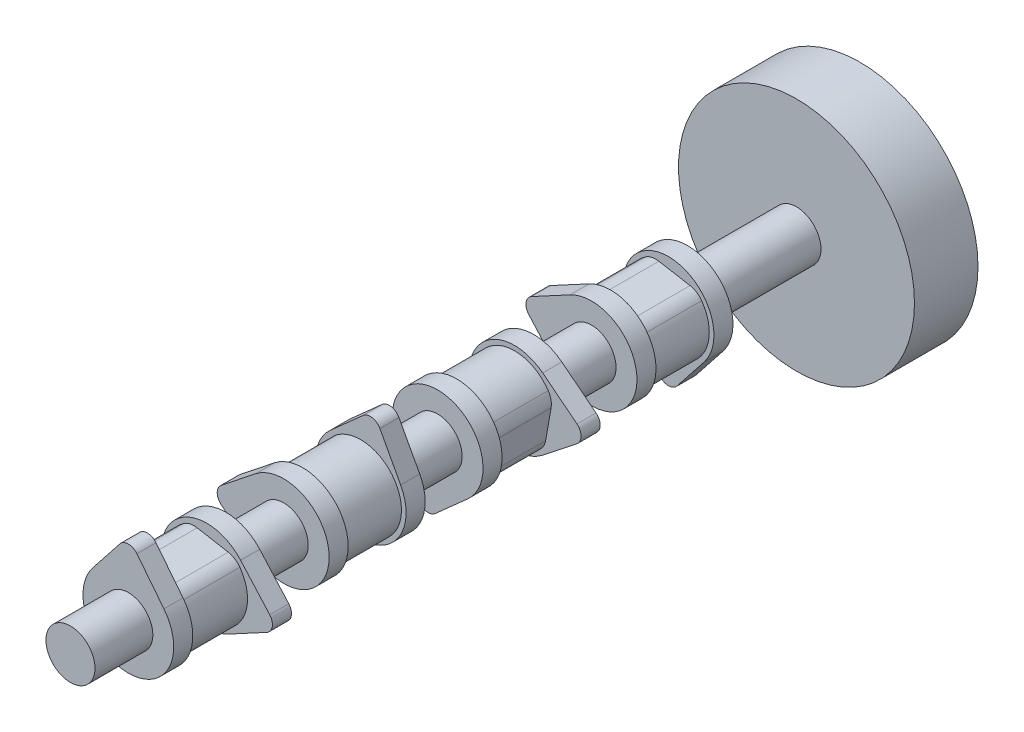
SolidWorks part; units mm, degrees
ref_plane "Alzado" through (0, 0, 0) normal (0, 0, 1) x (1, 0, 0)
ref_plane "Planta" through (0, 0, 0) normal (0, 1, 0) x (1, 0, 0)
ref_plane "Vista lateral" through (0, 0, 0) normal (1, 0, 0) x (0, 0, -1)
sketch "Croquis1" plane through (0, 0, 0) normal (0, 0, 1) x (1, 0, 0)
  circle A0 centre (0, 0) radius 65
  dimension "D1" = 130
extrude "Saliente-Extruir2" add sketch "Croquis1" along normal blind 35
sketch "Croquis2" plane through (0, 0, 35) normal (0, 0, 1) x (1, 0, 0)
  circle A0 centre (0, 0) radius 13.5
  dimension "D1" = 27
extrude "Saliente-Extruir3" add sketch "Croquis2" along normal blind 400
ref_plane "Plano1" through (0, 0, 392.6) normal (0, 0, 1) x (1, 0, 0)
sketch "Croquis3" plane through (0, 0, 392.6) normal (0, 0, 1) x (1, 0, 0)
  line L0 (0, -25) -> (0, 36.65) construction
  line L3 (-19.617, 15.4976) -> (-4.7081, 34.3694)
  line L4 (4.7081, 34.3694) -> (19.617, 15.4976)
  line L5 (0, 0) -> (7.2218, 0) construction
  circle A0 centre (0, 0) radius 13.5
  arc A1 (-19.617, 15.4976) -> (19.617, 15.4976) centre (0, 0) ccw
  arc A2 (4.7081, 34.3694) -> (-4.7081, 34.3694) centre (0, 30.65) ccw
  dimension "D1" = 50
  dimension "D2" = 27
  dimension "D4" = 6
  dimension "D3" = 61.65
extrude "Saliente-Extruir4" add sketch "Croquis3" along normal blind 10.5
ref_plane "Plano2" through (0, 0, 349.4) normal (0, 0, 1) x (1, 0, 0)
sketch "Croquis4" plane through (0, 0, 349.4) normal (0, 0, 1) x (1, 0, 0)
  line L0 (-24.6202, 4.3412) -> (36.0932, -6.3642) construction
  line L1 (18.6686, 16.6278) -> (34.6648, -1.3316)
  line L2 (33.0297, -10.6047) -> (11.8557, -22.0101)
  line L3 (0, 0) -> (7.2218, 0) construction
  circle A0 centre (0, 0) radius 13.5
  arc A1 (18.6686, 16.6278) -> (11.8557, -22.0101) centre (0, 0) ccw
  arc A2 (33.0297, -10.6047) -> (34.6648, -1.3316) centre (30.1844, -5.3223) ccw
  dimension "D1" = 50
  dimension "D2" = 27
  dimension "D3" = 6
  dimension "D4" = 61.65
  dimension "D5" = 10
extrude "Saliente-Extruir6" add sketch "Croquis4" along normal blind 10.5
ref_plane "Plano3" through (0, 0, 307) normal (0, 0, 1) x (1, 0, 0)
ref_plane "Plano4" through (0, 0, 264.6) normal (0, 0, 1) x (1, 0, 0)
ref_plane "Plano5" through (0, 0, 222.2) normal (0, 0, 1) x (1, 0, 0)
ref_plane "Plano6" through (0, 0, 179.8) normal (0, 0, 1) x (1, 0, 0)
ref_plane "Plano7" through (0, 0, 137.4) normal (0, 0, 1) x (1, 0, 0)
ref_plane "Plano8" through (0, 0, 95) normal (0, 0, 1) x (1, 0, 0)
sketch "Croquis5" plane through (0, 0, 307) normal (0, 0, 1) x (1, 0, 0)
  line L0 (25, 0) -> (-36.65, 0) construction
  line L1 (-15.4976, -19.617) -> (-34.3694, -4.7081)
  line L2 (-34.3694, 4.7081) -> (-15.4976, 19.617)
  line L3 (0, 0) -> (7.246, 0) construction
  circle A0 centre (0, 0) radius 13.5
  arc A1 (-15.4976, -19.617) -> (-15.4976, 19.617) centre (0, 0) ccw
  arc A2 (-34.3694, 4.7081) -> (-34.3694, -4.7081) centre (-30.65, 0) ccw
  point P10 (0, 0)
  dimension "D1" = 50
  dimension "D2" = 27
  dimension "D3" = 6
  dimension "D4" = 61.65
  dimension "D5" = 180
extrude "Saliente-Extruir7" add sketch "Croquis5" along normal blind 10.5
sketch "Croquis6" plane through (0, 0, 264.6) normal (0, 0, 1) x (1, 0, 0)
  line L0 (-4.3412, -24.6202) -> (6.3642, 36.0932) construction
  line L1 (-16.6278, 18.6686) -> (1.3316, 34.6648)
  line L2 (10.6047, 33.0297) -> (22.0101, 11.8557)
  line L3 (0, 0) -> (7.2218, 0) construction
  circle A0 centre (0, 0) radius 13.5
  arc A1 (-16.6278, 18.6686) -> (22.0101, 11.8557) centre (0, 0) ccw
  arc A2 (10.6047, 33.0297) -> (1.3316, 34.6648) centre (5.3223, 30.1844) ccw
  point P10 (0, 0)
  dimension "D1" = 50
  dimension "D2" = 27
  dimension "D3" = 6
  dimension "D4" = 61.65
  dimension "D5" = 80
extrude "Saliente-Extruir8" add sketch "Croquis6" along normal blind 10.5
sketch "Croquis7" plane through (0, 0, 222.2) normal (0, 0, 1) x (1, 0, 0)
  line L0 (4.3412, 24.6202) -> (-6.3642, -36.0932) construction
  line L1 (16.6278, -18.6686) -> (-1.3316, -34.6648)
  line L2 (-10.6047, -33.0297) -> (-22.0101, -11.8557)
  line L3 (0, 0) -> (7.2218, 0) construction
  circle A0 centre (0, 0) radius 13.5
  arc A1 (16.6278, -18.6686) -> (-22.0101, -11.8557) centre (0, 0) ccw
  arc A2 (-10.6047, -33.0297) -> (-1.3316, -34.6648) centre (-5.3223, -30.1844) ccw
  point P10 (0, 0)
  dimension "D1" = 50
  dimension "D2" = 27
  dimension "D3" = 6
  dimension "D4" = 61.65
  dimension "D5" = 260
extrude "Saliente-Extruir9" add sketch "Croquis7" along normal blind 10.5
sketch "Croquis8" plane through (0, 0, 179.8) normal (0, 0, 1) x (1, 0, 0)
  line L0 (-25, 0) -> (36.65, 0) construction
  line L1 (15.4976, 19.617) -> (34.3694, 4.7081)
  line L2 (34.3694, -4.7081) -> (15.4976, -19.617)
  line L3 (0, 0) -> (-65.5159, 0) construction
  circle A0 centre (0, 0) radius 13.5
  arc A1 (15.4976, 19.617) -> (15.4976, -19.617) centre (0, 0) ccw
  arc A2 (34.3694, -4.7081) -> (34.3694, 4.7081) centre (30.65, 0) ccw
  point P10 (0, 0)
  dimension "D1" = 50
  dimension "D2" = 27
  dimension "D3" = 6
  dimension "D4" = 61.65
  dimension "D5" = 180
extrude "Saliente-Extruir10" add sketch "Croquis8" along normal blind 10.5
sketch "Croquis9" plane through (0, 0, 137.4) normal (0, 0, 1) x (1, 0, 0)
  line L0 (24.6202, -4.3412) -> (-36.0932, 6.3642) construction
  line L1 (-18.6686, -16.6278) -> (-34.6648, 1.3316)
  line L2 (-33.0297, 10.6047) -> (-11.8557, 22.0101)
  line L3 (0, 0) -> (-72.796, 0) construction
  circle A0 centre (0, 0) radius 13.5
  arc A1 (-18.6686, -16.6278) -> (-11.8557, 22.0101) centre (0, 0) ccw
  arc A2 (-33.0297, 10.6047) -> (-34.6648, 1.3316) centre (-30.1844, 5.3223) ccw
  point P10 (0, 0)
  dimension "D1" = 50
  dimension "D2" = 27
  dimension "D3" = 6
  dimension "D4" = 61.65
  dimension "D5" = 10
extrude "Saliente-Extruir11" add sketch "Croquis9" along normal blind 10.5
sketch "Croquis10" plane through (0, 0, 95) normal (0, 0, 1) x (1, 0, 0)
  line L0 (0, 25) -> (0, -36.65) construction
  line L1 (19.617, -15.4976) -> (4.7081, -34.3694)
  line L2 (-4.7081, -34.3694) -> (-19.617, -15.4976)
  line L3 (0, 0) -> (-74.8277, 0) construction
  circle A0 centre (0, 0) radius 13.5
  arc A1 (19.617, -15.4976) -> (-19.617, -15.4976) centre (0, 0) ccw
  arc A2 (-4.7081, -34.3694) -> (4.7081, -34.3694) centre (0, -30.65) ccw
  point P10 (0, 0)
  dimension "D1" = 50
  dimension "D2" = 27
  dimension "D3" = 6
  dimension "D4" = 61.65
  dimension "D5" = 90
extrude "Saliente-Extruir12" add sketch "Croquis10" along normal blind 10.5
sketch "Croquis11" plane through (0, 0, 359.9) normal (0, 0, 1) x (1, 0, 0)
  line L0 (-5.3022, 20.1174) -> (11.863, 17.0907)
  line L1 (0, 0) -> (11.6898, 0) construction
  line L2 (0, 0) -> (3.2804, 18.6041) construction
  line L3 (0, 0) -> (8.2085, -1.4474) construction
  arc A0 (-12.6923, 18.5178) -> (18.2603, 13.06) centre (0, 0) ccw
  arc A1 (11.863, 17.0907) -> (18.2603, 13.06) centre (10.1265, 7.2426) cw
  arc A2 (-5.3022, 20.1174) -> (-12.6923, 18.5178) centre (-7.0387, 10.2693) ccw
  point P5 (0, -22.45)
  dimension "D1" = 44.9
  dimension "D3" = 10
  dimension "D2" = 41
  dimension "D4" = 18.8911
  dimension "D5" = 10
extrude "Saliente-Extruir13" add sketch "Croquis11" along normal up to surface (32.7 mm away) up to face at (0, 15.3792, 392.6)
sketch "Croquis12" plane through (0, 0, 275.1) normal (0, 0, 1) x (1, 0, 0)
  line L0 (-20.1174, -5.3022) -> (-17.0907, 11.863)
  line L1 (0, 0) -> (14.5214, 0) construction
  line L2 (0, 0) -> (-18.6041, 3.2804) construction
  line L3 (0, 0) -> (1.5862, 8.9956) construction
  arc A0 (-18.5178, -12.6923) -> (-13.06, 18.2603) centre (0, 0) ccw
  arc A1 (-17.0907, 11.863) -> (-13.06, 18.2603) centre (-7.2426, 10.1265) cw
  arc A2 (-20.1174, -5.3022) -> (-18.5178, -12.6923) centre (-10.2693, -7.0387) ccw
  point P4 (22.45, 0)
  point P11 (0, 0)
  point P13 (7.8955, 3.4904)
  point P14 (8.6729, 2.8665)
  dimension "D1" = 44.9
  dimension "D3" = 10
  dimension "D2" = 41
  dimension "D4" = 80
  dimension "D5" = 18.8911
extrude "Saliente-Extruir14" add sketch "Croquis12" along normal up to surface (31.9 mm away) up to face at (-15.3792, 0, 307)
sketch "Croquis14" plane through (0, 0, 190.3) normal (0, 0, 1) x (1, 0, 0)
  line L0 (20.1174, 5.3022) -> (17.0907, -11.863)
  line L1 (0, 0) -> (9.7004, 0) construction
  line L2 (0, 0) -> (18.6041, -3.2804) construction
  line L3 (0, 0) -> (1.0092, 5.7235) construction
  line L6 (0, 0) -> (-6.3642, -36.0932) construction
  arc A0 (18.5178, 12.6923) -> (13.06, -18.2603) centre (0, 0) ccw
  arc A1 (17.0907, -11.863) -> (13.06, -18.2603) centre (7.2426, -10.1265) cw
  arc A2 (20.1174, 5.3022) -> (18.5178, 12.6923) centre (10.2693, 7.0387) ccw
  arc A3 (-10.6047, -33.0297) -> (-1.3316, -34.6648) centre (-5.3223, -30.1844) ccw construction
  point P4 (-22.45, 0)
  dimension "D1" = 44.9
  dimension "D3" = 10
  dimension "D2" = 41
  dimension "D5" = 18.8911
extrude "Saliente-Extruir15" add sketch "Croquis14" along normal up to surface (31.9 mm away) up to face at (-2.6706, -15.1456, 222.2)
sketch "Croquis15" plane through (0, 0, 105.5) normal (0, 0, 1) x (1, 0, 0)
  line L0 (-5.3022, 20.1174) -> (11.863, 17.0907)
  line L1 (0, 0) -> (10.6649, 0) construction
  line L2 (0, 0) -> (3.2804, 18.6041) construction
  line L3 (0, 0) -> (8.2085, -1.4474) construction
  line L4 (0, 0) -> (-36.0932, 6.3642) construction
  arc A0 (-12.6923, 18.5178) -> (18.2603, 13.06) centre (0, 0) ccw
  arc A1 (11.863, 17.0907) -> (18.2603, 13.06) centre (10.1265, 7.2426) cw
  arc A2 (-5.3022, 20.1174) -> (-12.6923, 18.5178) centre (-7.0387, 10.2693) ccw
  arc A3 (-33.0297, 10.6047) -> (-34.6648, 1.3316) centre (-30.1844, 5.3223) ccw construction
  point P4 (0, -22.45)
  dimension "D1" = 44.9
  dimension "D3" = 10
  dimension "D2" = 41
  dimension "D5" = 18.8911
extrude "Saliente-Extruir16" add sketch "Croquis15" along normal up to surface (31.9 mm away) up to face at (-15.1456, 2.6706, 137.4)
